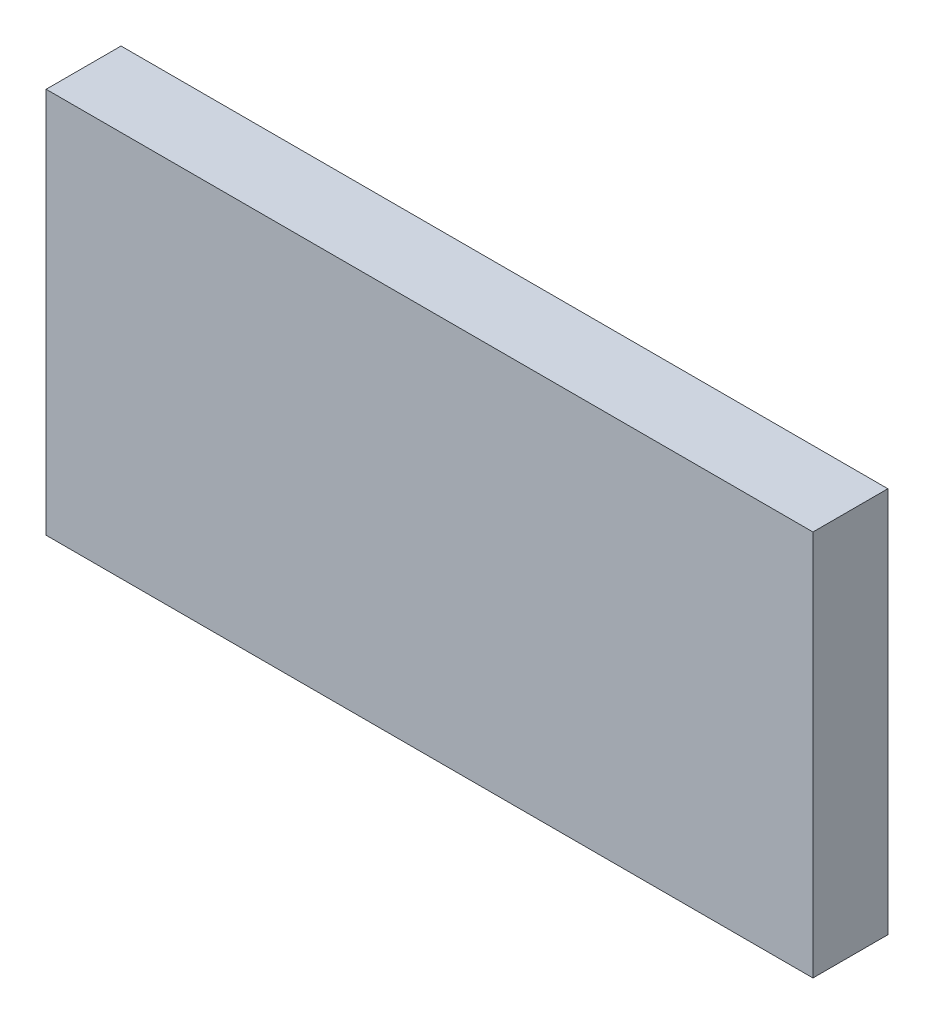
SolidWorks part; units mm, degrees
ref_plane "Ebene vorne" through (0, 0, 0) normal (0, 0, 1) x (1, 0, 0)
ref_plane "Ebene oben" through (0, 0, 0) normal (0, 1, 0) x (1, 0, 0)
ref_plane "Ebene rechts" through (0, 0, 0) normal (1, 0, 0) x (0, 0, -1)
sketch "Skizze1" plane through (0, 0, 0) normal (0, 0, 1) x (1, 0, 0)
  line L0 (-5.1562, 2.54) -> (5.08, 2.54)
  line L1 (5.08, 2.54) -> (5.08, -2.6162)
  line L2 (5.08, -2.6162) -> (-5.1562, -2.6162)
  line L3 (-5.1562, -2.6162) -> (-5.1562, 2.54)
extrude "Component_Outline" add sketch "Skizze1" along normal blind 1 separate body
sketch3d "3D-Skizze1"
  line L0 (0, 0, 0) -> (1, 0, 0)
  line L1 (0, 0, 0) -> (0, 1, 0)
  line L2 (0, 0, 0) -> (0, 0, 1)
  point P0 (0, 0, 0)
